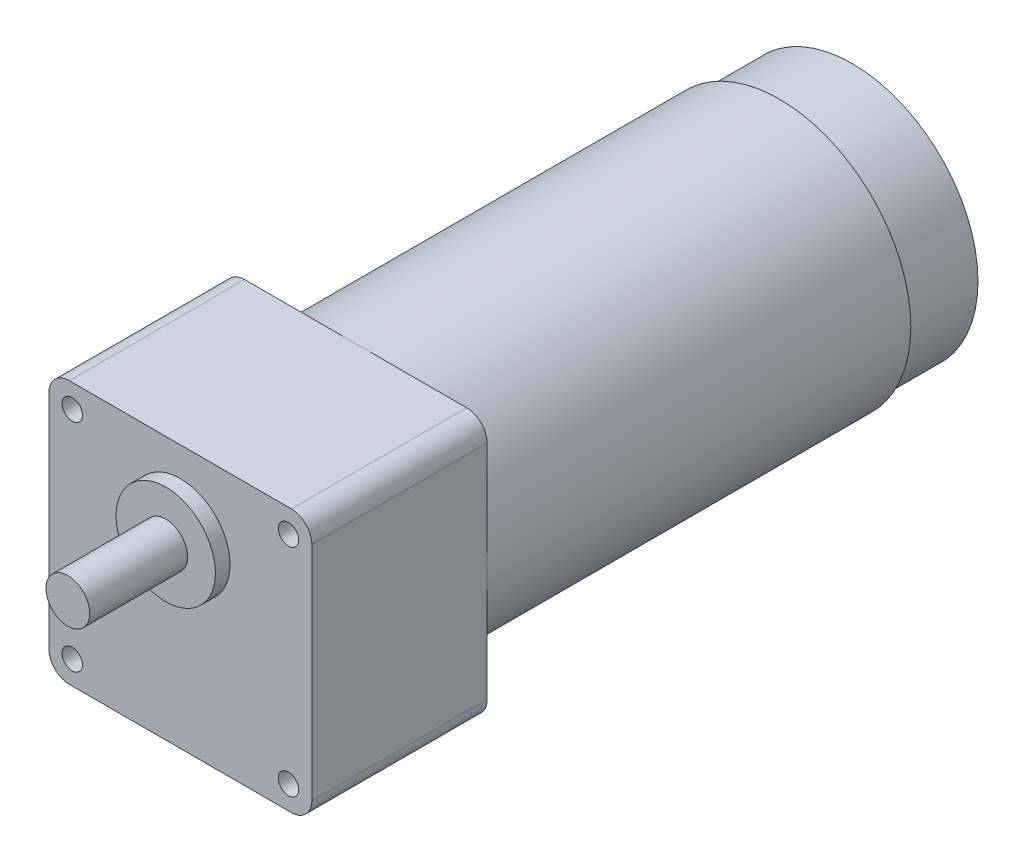
SolidWorks part; units mm, degrees
ref_plane "Front Plane" through (0, 0, 0) normal (0, 0, 1) x (1, 0, 0)
ref_plane "Top Plane" through (0, 0, 0) normal (0, 1, 0) x (1, 0, 0)
ref_plane "Right Plane" through (0, 0, 0) normal (1, 0, 0) x (0, 0, -1)
sketch "Sketch1" plane through (0, 0, 0) normal (0, 0, 1) x (1, 0, 0)
  line L1 (-45, 45) -> (45, 45)
  line L2 (-45, 45) -> (-45, -45)
  line L3 (-45, -45) -> (45, -45)
  line L4 (45, 45) -> (45, -45)
  line L5 (-45, 45) -> (45, -45) construction
  line L6 (-45, -45) -> (45, 45) construction
  point P0 (0, 0)
  dimension "D1" = 90
  dimension "D2" = 90
extrude "Boss-Extrude1" add sketch "Sketch1" along normal blind 60
sketch "Sketch2" plane through (0, 0, 0) normal (0, 0, -1) x (-1, 0, 0)
  circle A0 centre (0, 0) radius 45
extrude "Boss-Extrude2" add sketch "Sketch2" along normal blind 170
sketch "Sketch3" plane through (0, 0, 60) normal (0, 0, 1) x (1, 0, 0)
  line L0 (0, 0) -> (0, 18) construction
  circle A0 centre (0, 18) radius 17
  dimension "D2" = 34
  dimension "D1" = 18
extrude "Boss-Extrude3" add sketch "Sketch3" along normal blind 5
sketch "Sketch4" plane through (0, 0, 65) normal (0, 0, 1) x (1, 0, 0)
  circle A0 centre (0, 18) radius 7.5
extrude "Boss-Extrude4" add sketch "Sketch4" along normal blind 33.5
sketch "Sketch5" plane through (0, 0, 60) normal (0, 0, 1) x (1, 0, 0)
  line L1 (-37, 37) -> (37, 37) construction
  line L2 (-37, 37) -> (-37, -37) construction
  line L3 (-37, -37) -> (37, -37) construction
  line L4 (37, 37) -> (37, -37) construction
  line L5 (-37, 37) -> (37, -37) construction
  line L6 (-37, -37) -> (37, 37) construction
  circle A0 centre (-37, 37) radius 3.5
  circle A1 centre (37, 37) radius 3.5
  circle A2 centre (37, -37) radius 3.5
  circle A3 centre (-37, -37) radius 3.5
  point P0 (0, 0)
  point P17 (0, 0)
  dimension "D1" = 74
  dimension "D2" = 4
extrude "Cut-Extrude1" cut sketch "Sketch5" against normal up to next
fillet "Fillet1" radius 7 4 edges at (45, -45, 30) (45, 45, 30) (-45, -45, 30) (-45, 45, 30)
sketch "Sketch6" plane through (0, 0, -170) normal (0, 0, -1) x (-1, 0, 0)
  circle A0 centre (0, 0) radius 45
  circle A1 centre (0, 0) radius 43
extrude "Cut-Extrude2" cut sketch "Sketch6" against normal blind 25
